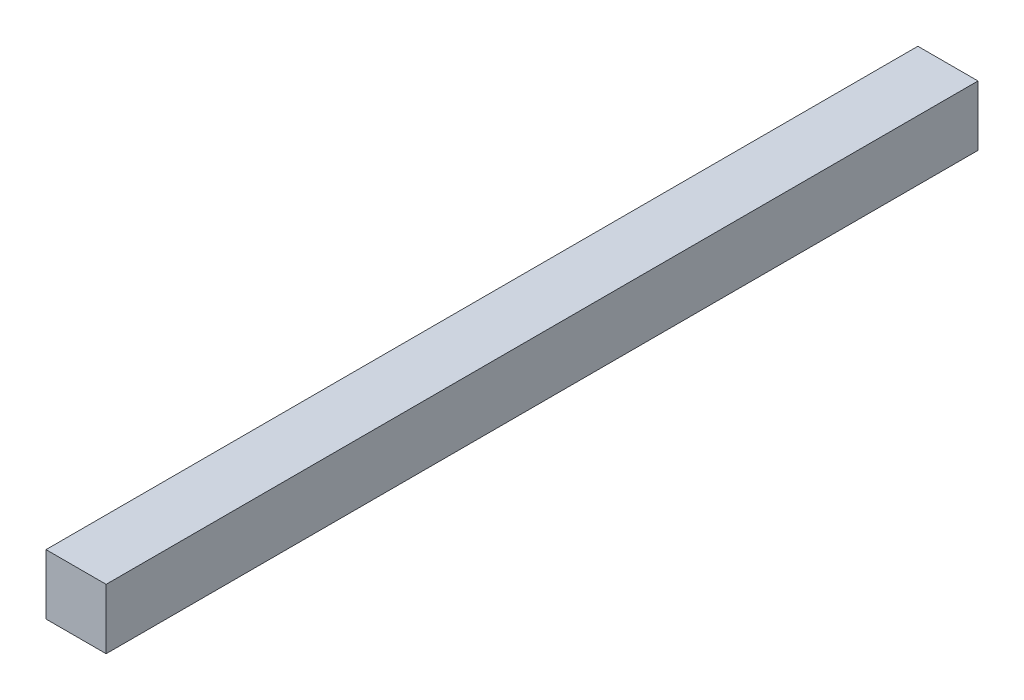
SolidWorks part; units mm, degrees
ref_plane "Front Plane" through (0, 0, 0) normal (0, 0, 1) x (1, 0, 0)
ref_plane "Top Plane" through (0, 0, 0) normal (0, 1, 0) x (1, 0, 0)
ref_plane "Right Plane" through (0, 0, 0) normal (1, 0, 0) x (0, 0, -1)
sketch "Sketch1" plane through (0, 0, 0) normal (0, 0, 1) x (1, 0, 0)
  line L1 (-10, -10) -> (10, -10)
  line L2 (-10, -10) -> (-10, 10)
  line L3 (-10, 10) -> (10, 10)
  line L4 (10, -10) -> (10, 10)
  line L5 (-10, -10) -> (10, 10) construction
  line L6 (-10, 10) -> (10, -10) construction
  point P0 (0, 0)
  dimension "D1" = 20
extrude "Boss-Extrude1" add sketch "Sketch1" along normal blind 290
